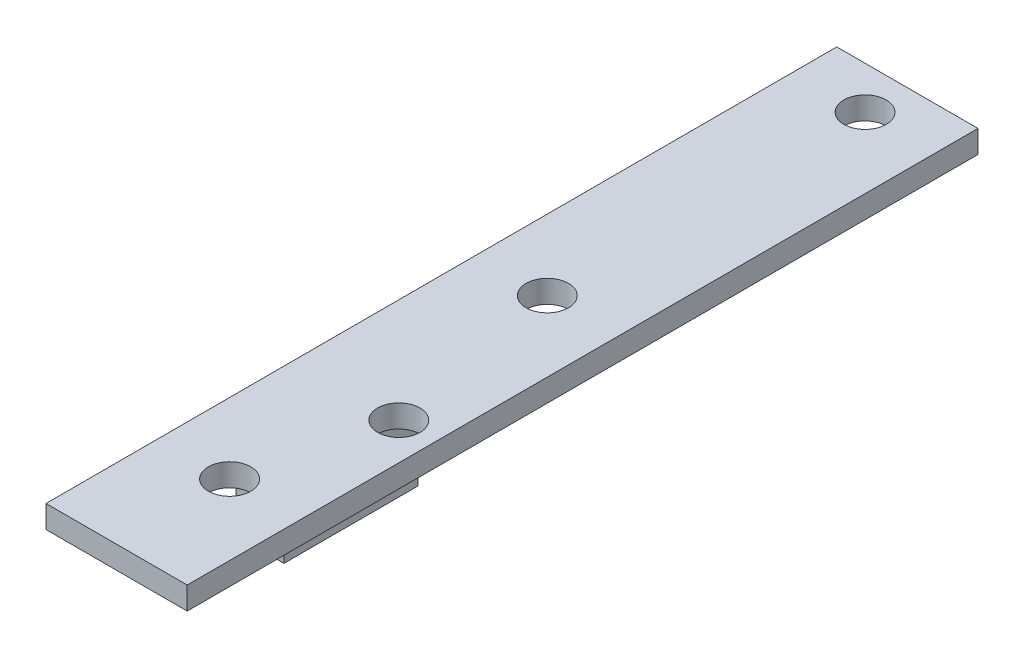
SolidWorks part; units mm, degrees
ref_plane "前视基准面" through (0, 0, 0) normal (0, 0, 1) x (1, 0, 0)
ref_plane "上视基准面" through (0, 0, 0) normal (0, 1, 0) x (1, 0, 0)
ref_plane "右视基准面" through (0, 0, 0) normal (1, 0, 0) x (0, 0, -1)
sketch "草图1" plane through (0, 0, 0) normal (0, 1, 0) x (1, 0, 0)
  line L0 (0, 0) -> (0, 28) construction
  line L1 (-5, 28) -> (5, 28)
  line L2 (-5, 28) -> (-5, -28)
  line L3 (-5, -28) -> (5, -28)
  line L4 (5, 28) -> (5, -28)
  line L5 (-5, 28) -> (5, -28) construction
  line L6 (-5, -28) -> (5, 28) construction
  circle A0 centre (2.385, -10.4) radius 1.5
  circle A1 centre (0, 25) radius 1.5
  circle A2 centre (0, 2.5) radius 1.5
  circle A3 centre (0, -20) radius 1.5
  point P0 (0, 0)
  dimension "D5" = 3
  dimension "D9" = 3
  dimension "D10" = 3
  dimension "D11" = 3
  dimension "D1" = 56
  dimension "D2" = 10
  dimension "D3" = 38.4
  dimension "D4" = 2.615
  dimension "D6" = 3
  dimension "D7" = 22.5
  dimension "D8" = 8
extrude "凸台-拉伸1" add sketch "草图1" along normal blind 1.6
sketch "草图2" plane through (0, 0, 0) normal (0, -1, 0) x (1, 0, 0)
  line L0 (7.9459, 10.4) -> (3.5046, 10.4) construction
  line L1 (-1, 5.65) -> (-4.4, 5.65)
  line L2 (-1, 5.65) -> (-1, 15.15)
  line L3 (-1, 15.15) -> (-4.4, 15.15)
  line L4 (-4.4, 5.65) -> (-4.4, 15.15)
  line L5 (-1, 5.65) -> (-4.4, 15.15) construction
  line L6 (-1, 15.15) -> (-4.4, 5.65) construction
  line L7 (-5, -28) -> (-5, 28) construction
  point P0 (-2.7, 10.4)
  point P5 (2.385, 10.4)
  point P9 (-7.9238, 7.3071)
  point P10 (0, 0)
  point P11 (-4.2403, 6.6222)
  dimension "D1" = 3.4
  dimension "D2" = 9.5
  dimension "D3" = 0.6
extrude "凸台-拉伸2" add sketch "草图2" along normal blind 6.5
